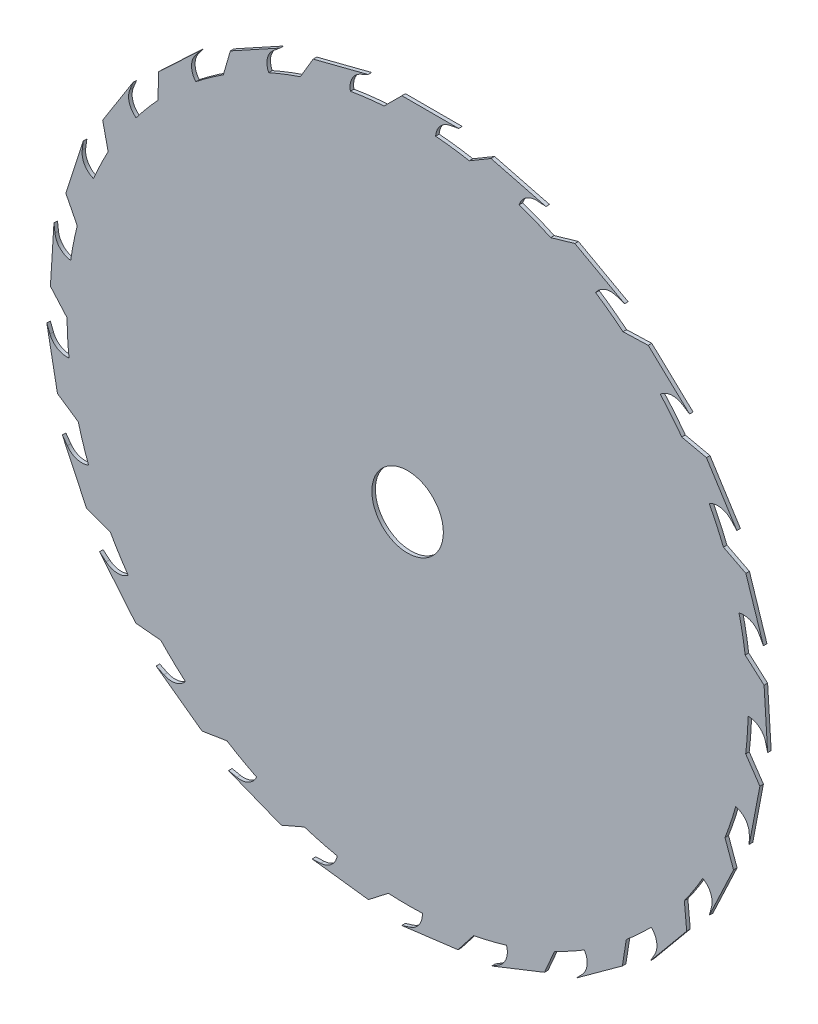
SolidWorks part; units mm, degrees
ref_plane "Front Plane" through (0, 0, 0) normal (0, 0, 1) x (1, 0, 0)
ref_plane "Top Plane" through (0, 0, 0) normal (0, 1, 0) x (1, 0, 0)
ref_plane "Right Plane" through (0, 0, 0) normal (1, 0, 0) x (0, 0, -1)
sketch "Sketch1" plane through (0, 0, 0) normal (0, 0, 1) x (1, 0, 0)
  circle A0 centre (0, 0) radius 152.4
  dimension "D1" = 304.8
extrude "Boss-Extrude1" add sketch "Sketch1" along normal blind 1.5875 contours A0
sketch "Sketch2" plane through (0, 0, 1.5875) normal (0, 0, 1) x (1, 0, 0)
  circle A0 centre (0, 0) radius 16.002
  dimension "D1" = 32.004
extrude "Cut-Extrude1" cut sketch "Sketch2" against normal up to next
sketch "Sketch4" plane through (0, 0, 1.5875) normal (0, 0, 1) x (1, 0, 0)
  line L0 (-12.7, 149.86) -> (-2.54, 160.02)
  line L1 (-2.54, 160.02) -> (22.86, 160.02)
  line L2 (22.86, 160.02) -> (19.1129, 159.3305)
  line L3 (12.7, 149.86) -> (-12.7, 149.86)
  arc A0 (19.1129, 159.3305) -> (12.7, 149.86) centre (20.5648, 151.4408) ccw
  point P8 (0, 149.86)
  dimension "D1" = 3.81
  dimension "D7" = 1.5808
  dimension "D2" = 25.4
  dimension "D3" = 10.16
  dimension "D4" = 25.4
  dimension "D5" = 160.02
  dimension "D6" = 45
extrude "Boss-Extrude2" add sketch "Sketch4" against normal up to surface (1.5875 mm away) up to face at (16.002, 0, 0)
pattern_circular "CirPattern1" count 25 over 360 about axis through (0, 0, 0) along (0, 0, 1) of "Boss-Extrude2"
